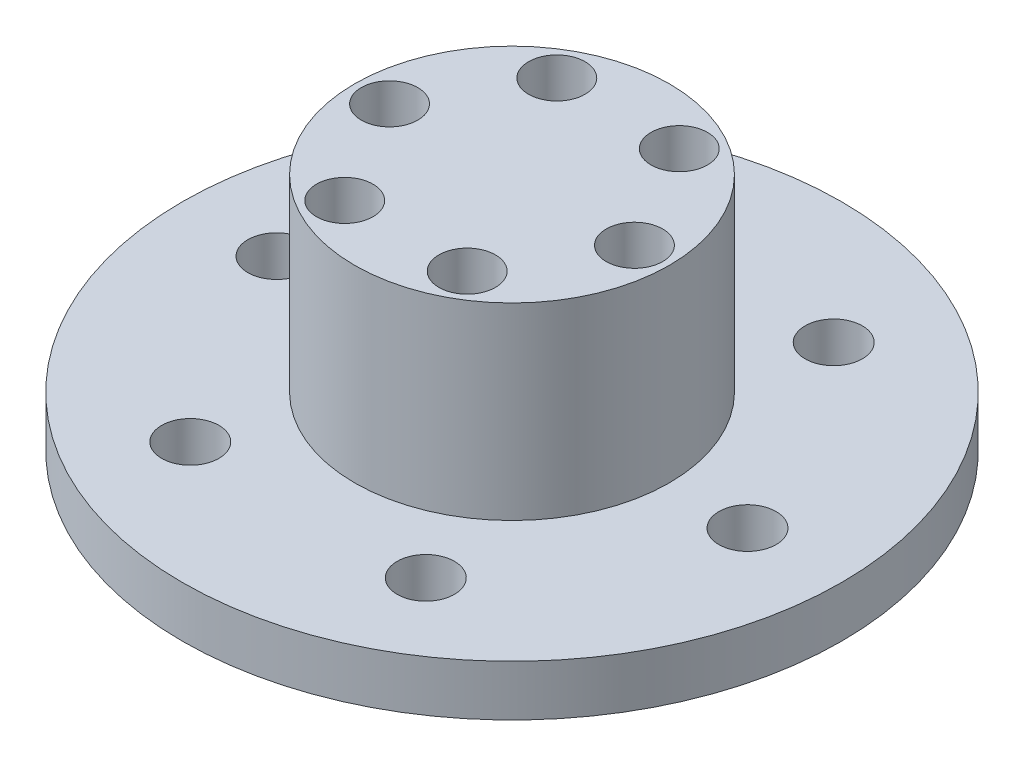
SolidWorks part; units mm, degrees
ref_plane "Alzado" through (0, 0, 0) normal (0, 0, 1) x (1, 0, 0)
ref_plane "Planta" through (0, 0, 0) normal (0, 1, 0) x (1, 0, 0)
ref_plane "Vista lateral" through (0, 0, 0) normal (1, 0, 0) x (0, 0, -1)
sketch "Croquis1" plane through (0, 0, 0) normal (0, 1, 0) x (1, 0, 0)
  circle A0 centre (0, 0) radius 12.5 construction
  circle A1 centre (12.5, 0) radius 1.52
  circle A2 centre (6.25, -10.8253) radius 1.52
  circle A3 centre (-6.25, -10.8253) radius 1.52
  circle A4 centre (-12.5, 0) radius 1.52
  circle A5 centre (-6.25, 10.8253) radius 1.52
  circle A6 centre (6.25, 10.8253) radius 1.52
  circle A7 centre (0, 0) radius 17.5
  point P17 (0, 0)
  dimension "D1" = 25
  dimension "D2" = 3.04
  dimension "D4" = 35
  dimension "D3" = 6
extrude "Saliente-Extruir1" add sketch "Croquis1" along normal blind 2.7
sketch "Croquis2" plane through (0, 2.7, 0) normal (0, 1, 0) x (1, 0, 0)
  circle A0 centre (0, 0) radius 8.35
  circle A1 centre (0, 0) radius 6.5 construction
  circle A2 centre (6.5, 0) radius 1.5
  circle A3 centre (3.25, -5.6292) radius 1.5
  circle A4 centre (-3.25, -5.6292) radius 1.5
  circle A5 centre (-6.5, 0) radius 1.5
  circle A6 centre (-3.25, 5.6292) radius 1.5
  circle A7 centre (3.25, 5.6292) radius 1.5
  point P18 (0, 0)
  dimension "D1" = 16.7
  dimension "D2" = 13
  dimension "D3" = 3
  dimension "D4" = 6
extrude "Saliente-Extruir2" add sketch "Croquis2" along normal blind 10
